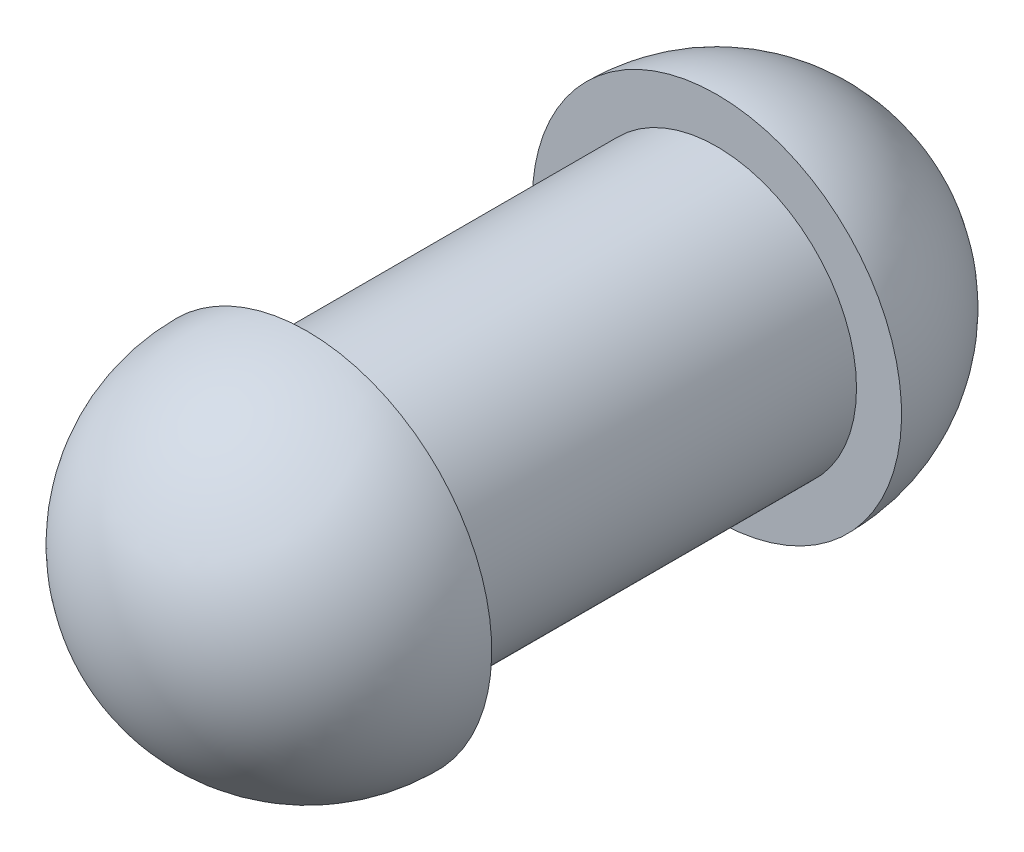
SolidWorks part; units mm, degrees
ref_plane "Front Plane" through (0, 0, 0) normal (0, 0, 1) x (1, 0, 0)
ref_plane "Top Plane" through (0, 0, 0) normal (0, 1, 0) x (1, 0, 0)
ref_plane "Right Plane" through (0, 0, 0) normal (1, 0, 0) x (0, 0, -1)
sketch "Sketch1" plane through (0, 0, 0) normal (0, 0, 1) x (1, 0, 0)
  circle A0 centre (0, 0) radius 15.5
  dimension "D1" = 31
extrude "Boss-Extrude1" add sketch "Sketch1" along normal mid plane 45.5
sketch "Sketch2" plane through (0, 0, 0) normal (1, 0, 0) x (0, 0, -1)
  line L0 (0, 0) -> (-63.0026, 0) construction
  line L1 (-22.75, 15.5) -> (-22.75, -15.5) construction
  line L2 (-43.25, 0) -> (-22.75, 0)
  line L3 (-22.75, 0) -> (-22.75, 20.5)
  arc A0 (-22.75, 20.5) -> (-43.25, 0) centre (-22.75, 0) ccw
  dimension "D1" = 20.5
revolve "Revolve1" add sketch "Sketch2" angle 360 about L0
mirror "Mirror1" about plane through (0, 0, 0) normal (0, 0, 1) of bodies 102
